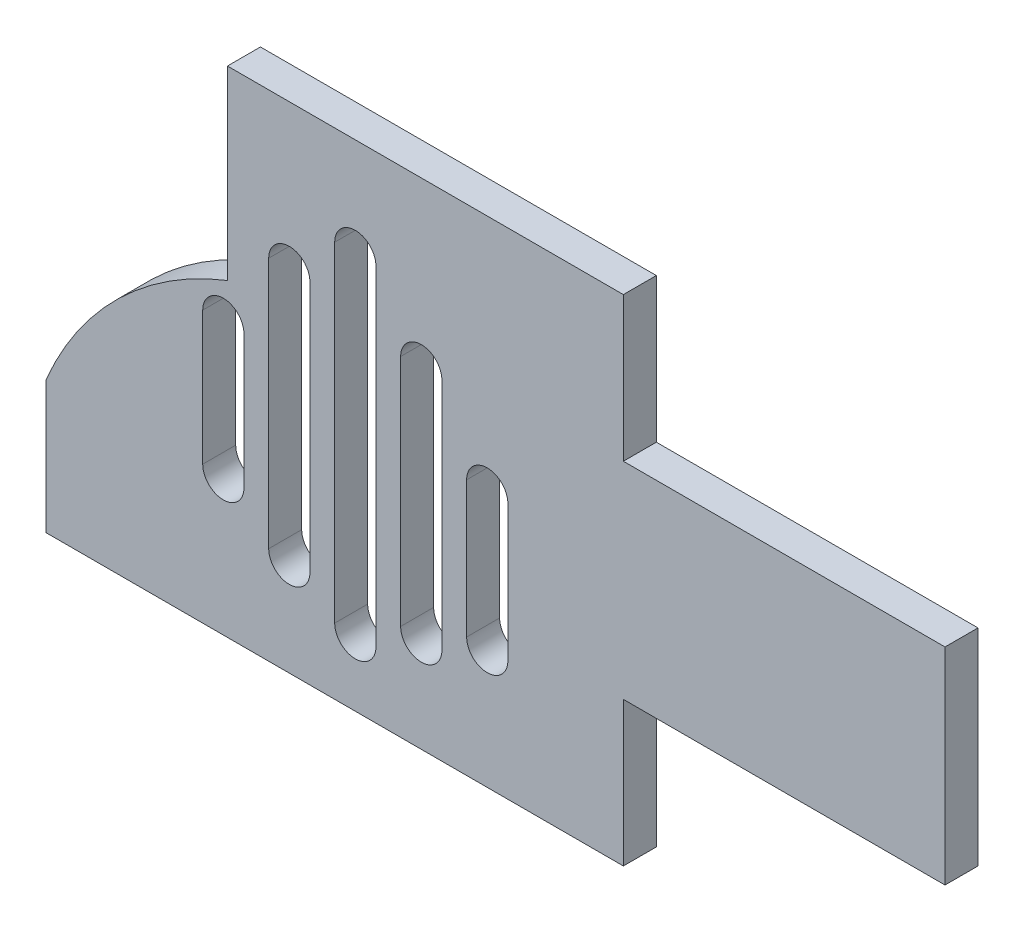
SolidWorks part; units mm, degrees
ref_plane "Front Plane" through (0, 0, 0) normal (0, 0, 1) x (1, 0, 0)
ref_plane "Top Plane" through (0, 0, 0) normal (0, 1, 0) x (1, 0, 0)
ref_plane "Right Plane" through (0, 0, 0) normal (1, 0, 0) x (0, 0, -1)
sketch "Sketch1" plane through (0, 0, 0) normal (0, 0, 1) x (1, 0, 0)
  line L0 (-4.1373, 38.9941) -> (-4.1373, -1.0059)
  line L6 (30.8627, 33.4941) -> (69.8627, 33.4941)
  line L9 (0.8627, 38.9941) -> (0.8627, -1.0059)
  line L12 (-12.1373, 33.3124) -> (-12.1373, 2.8098)
  line L15 (-7.1373, 33.3124) -> (-7.1373, 2.8098)
  line L18 (-15.1373, 23.8613) -> (-15.1373, 7.6834)
  line L21 (30.8627, 8.4941) -> (69.8627, 8.4941)
  line L26 (-39.1373, 7.0374) -> (-39.1373, -9.0059)
  line L62 (-17.1373, 50.9941) -> (-17.1373, 28.4723)
  line L66 (30.8627, 50.9941) -> (30.8627, 33.4941)
  line L68 (69.8627, 33.4941) -> (69.8627, 8.4941)
  line L70 (30.8627, 8.4941) -> (30.8627, -9.0059)
  line L71 (30.8627, 50.9941) -> (-17.1373, 50.9941)
  line L72 (30.8627, -9.0059) -> (-39.1373, -9.0059)
  line L75 (-20.1373, 23.8613) -> (-20.1373, 7.6834)
  line L77 (3.8627, 30.9941) -> (3.8627, 2.6474)
  line L79 (8.8627, 30.9941) -> (8.8627, 2.6474)
  line L80 (11.8627, 22.0483) -> (11.8627, 5.5385)
  line L81 (16.8627, 22.0483) -> (16.8627, 5.5385)
  circle A13 centre (-1.6373, 38.9941) radius 2.5 construction
  circle A14 centre (-1.6373, -1.0059) radius 2.5 construction
  arc A15 (-4.1373, 38.9941) -> (0.8627, 38.9941) centre (-1.6373, 38.9941) cw
  arc A16 (0.8627, -1.0059) -> (-4.1373, -1.0059) centre (-1.6373, -1.0059) cw
  circle A17 centre (6.3627, 30.9941) radius 2.5 construction
  circle A18 centre (6.3627, 2.6474) radius 2.5 construction
  circle A19 centre (-9.6373, 33.3124) radius 2.5 construction
  circle A20 centre (-9.6373, 2.8098) radius 2.5 construction
  circle A21 centre (-17.6373, 23.8613) radius 2.5 construction
  circle A22 centre (-17.6373, 7.6834) radius 2.5 construction
  circle A23 centre (14.3627, 22.0483) radius 2.5 construction
  circle A24 centre (14.3627, 5.5385) radius 2.5 construction
  arc A27 (-12.1373, 33.3124) -> (-7.1373, 33.3124) centre (-9.6373, 33.3124) cw
  arc A28 (-15.1373, 23.8613) -> (-20.1373, 23.8613) centre (-17.6373, 23.8613) ccw
  arc A29 (-20.1373, 7.6834) -> (-15.1373, 7.6834) centre (-17.6373, 7.6834) ccw
  arc A30 (-12.1373, 2.8098) -> (-7.1373, 2.8098) centre (-9.6373, 2.8098) ccw
  arc A31 (3.8627, 2.6474) -> (8.8627, 2.6474) centre (6.3627, 2.6474) ccw
  arc A32 (11.8627, 5.5385) -> (16.8627, 5.5385) centre (14.3627, 5.5385) ccw
  arc A33 (16.8627, 22.0483) -> (11.8627, 22.0483) centre (14.3627, 22.0483) ccw
  arc A34 (8.8627, 30.9941) -> (3.8627, 30.9941) centre (6.3627, 30.9941) ccw
  arc A35 (-17.1373, 28.4723) -> (-39.1373, 7.0374) centre (-2.9278, -8.1193) ccw
  point P0 (0, 0)
  dimension "D3" = 5
  dimension "D4" = 8
  dimension "D5" = 8
  dimension "D6" = 8
  dimension "D7" = 8
  dimension "D9" = 12
  dimension "D8" = 25
  dimension "D10" = 15.5
  dimension "D11" = 60
  dimension "D12" = 8
  dimension "D13" = 22
  dimension "D15" = 39
  dimension "D16" = 48
  dimension "D23" = 40
extrude "Boss-Extrude1" add sketch "Sketch1" along normal blind 4
sketch "Sketch2" plane through (0, 0, 0) normal (0, 0, -1) x (-1, 0, 0)
  line L0 (-69.8627, 20.9941) -> (-30.8627, 20.9941) construction
  line L1 (-69.8627, 8.4941) -> (-69.8627, 33.4941) construction
  point P4 (0, 0)
equation "\"m\"= 3mm"
